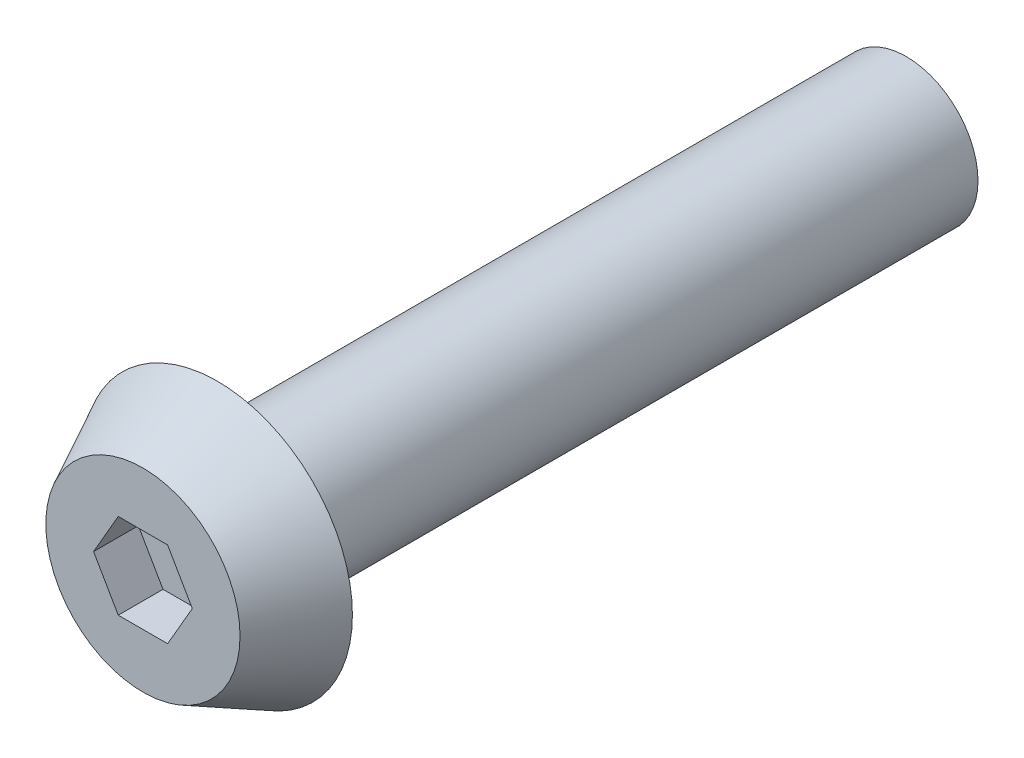
SolidWorks part; units mm, degrees
ref_plane "Front Plane" through (0, 0, 0) normal (0, 0, 1) x (1, 0, 0)
ref_plane "Top Plane" through (0, 0, 0) normal (0, 1, 0) x (1, 0, 0)
ref_plane "Right Plane" through (0, 0, 0) normal (1, 0, 0) x (0, 0, -1)
sketch "SK_shank" plane through (0, 0, 0) normal (0, 0, 1) x (1, 0, 0)
  circle A0 centre (0, 0) radius 1.25
extrude "Shank" add sketch "SK_shank" against normal blind 12
sketch "SK_head" plane through (0, 0, 0) normal (0, 0, 1) x (1, 0, 0)
  circle A0 centre (0, 0) radius 2.35
extrude "Head" add sketch "SK_head" along normal blind 1.3 draft 26.846
sketch "SK_socket" plane through (0, 0, 0) normal (0, 0, 1) x (1, 0, 0)
  line L0 (0.8603, 0) -> (0.4301, -0.745)
  line L1 (0.4301, -0.745) -> (-0.4301, -0.745)
  line L2 (-0.4301, -0.745) -> (-0.8603, 0)
  line L3 (-0.8603, 0) -> (-0.4301, 0.745)
  line L4 (-0.4301, 0.745) -> (0.4301, 0.745)
  line L5 (0.4301, 0.745) -> (0.8603, 0)
extrude "Socket" cut sketch "SK_socket" along normal blind 1.28 from offset 0.52
